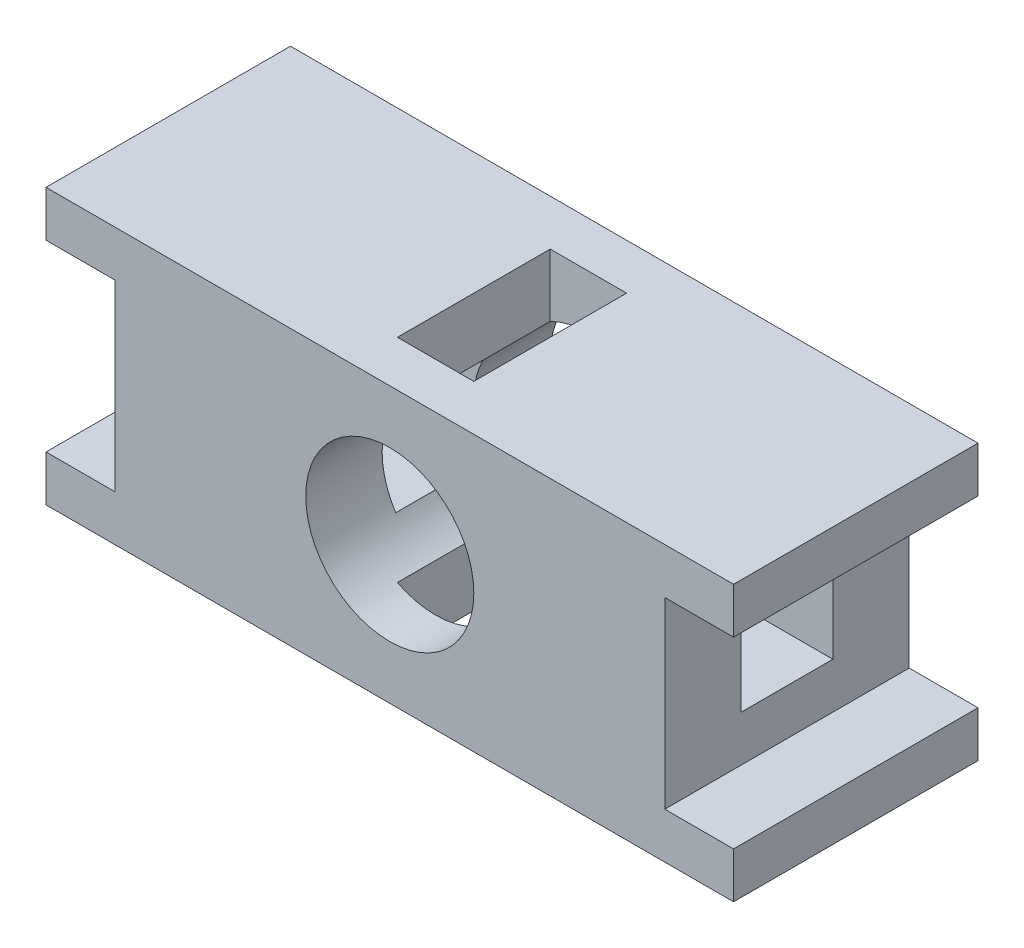
SolidWorks part; units mm, degrees
ref_plane "Спереди" through (0, 0, 0) normal (0, 0, 1) x (1, 0, 0)
ref_plane "Сверху" through (0, 0, 0) normal (0, 1, 0) x (1, 0, 0)
ref_plane "Справа" through (0, 0, 0) normal (1, 0, 0) x (0, 0, -1)
sketch "Эскиз2" plane through (0, 0, 0) normal (0, 0, 1) x (1, 0, 0)
  line L1 (-45, -18) -> (45, -18)
  line L2 (-45, -18) -> (-45, 18)
  line L3 (-45, 18) -> (45, 18)
  line L4 (45, -18) -> (45, 18)
  line L5 (-45, -18) -> (45, 18) construction
  line L6 (-45, 18) -> (45, -18) construction
  point P0 (0, 0)
  dimension "D1" = 90
  dimension "D2" = 36
extrude "Бобышка-Вытянуть1" add sketch "Эскиз2" along normal blind 32
sketch "Эскиз3" plane through (0, 0, 32) normal (0, 0, 1) x (1, 0, 0)
  line L0 (-45, 12) -> (-36, 12)
  line L1 (-45, 18) -> (-45, -18) construction
  line L2 (45, 18) -> (-45, 18) construction
  line L3 (-36, 12) -> (-36, -12)
  line L4 (-36, -12) -> (-45, -12)
  line L5 (-45, -18) -> (45, -18) construction
  line L6 (-45, 12) -> (-45, -12)
  dimension "D1" = 9
  dimension "D2" = 6
  dimension "D3" = 24
  dimension "D4" = 9
  dimension "D5" = 6
extrude "Вырез-Вытянуть1" cut sketch "Эскиз3" against normal through all
sketch "Эскиз4" plane through (0, 0, 32) normal (0, 0, 1) x (1, 0, 0)
  line L0 (45, 18) -> (-45, 18) construction
  line L1 (36, 12) -> (45, 12)
  line L2 (36, 12) -> (36, -12)
  line L3 (36, -12) -> (45, -12)
  line L4 (45, 12) -> (45, -12)
  line L5 (36, 12) -> (45, -12) construction
  line L6 (36, -12) -> (45, 12) construction
  line L7 (-45, -18) -> (45, -18) construction
  line L8 (-36, -12) -> (-36, 12) construction
  line L9 (45, -18) -> (45, 18) construction
  point P0 (40.5, 0)
  dimension "D1" = 24
  dimension "D2" = 9
  dimension "D3" = 6
  dimension "D4" = 6
  dimension "D5" = 72
  dimension "D6" = 9
extrude "Вырез-Вытянуть2" cut sketch "Эскиз4" against normal through all
sketch "Эскиз6" plane through (0, 0, 32) normal (0, 0, 1) x (1, 0, 0)
  circle A0 centre (0, 0) radius 11
  dimension "D1" = 22
extrude "Вырез-Вытянуть3" cut sketch "Эскиз6" against normal through all
sketch "Эскиз7" plane through (0, 18, 0) normal (0, 1, 0) x (1, 0, 0)
  line L0 (45, 0) -> (-45, 0) construction
  line L1 (-5, -6) -> (5, -6)
  line L2 (-5, -6) -> (-5, -26)
  line L3 (-5, -26) -> (5, -26)
  line L4 (5, -6) -> (5, -26)
  line L5 (-5, -6) -> (5, -26) construction
  line L6 (-5, -26) -> (5, -6) construction
  line L7 (45, -32) -> (-45, -32) construction
  line L8 (-45, -32) -> (-45, 0) construction
  line L9 (45, -32) -> (45, 0) construction
  point P0 (0, -16)
  dimension "D1" = 10
  dimension "D2" = 20
  dimension "D3" = 6
  dimension "D4" = 6
  dimension "D5" = 40
  dimension "D6" = 40
extrude "Вырез-Вытянуть4" cut sketch "Эскиз7" against normal through all
sketch "Эскиз9" plane through (-36, 0, 0) normal (-1, 0, 0) x (0, 0, 1)
  line L0 (0, 12) -> (32, 12) construction
  line L1 (10, 6) -> (22, 6)
  line L2 (10, 6) -> (10, -6)
  line L3 (10, -6) -> (22, -6)
  line L4 (22, 6) -> (22, -6)
  line L5 (10, 6) -> (22, -6) construction
  line L6 (10, -6) -> (22, 6) construction
  line L7 (0, -12) -> (32, -12) construction
  line L8 (0, -12) -> (0, 12) construction
  line L9 (32, -12) -> (32, 12) construction
  point P0 (16, 0)
  dimension "D1" = 12
  dimension "D2" = 12
  dimension "D3" = 6
  dimension "D4" = 6
  dimension "D5" = 10
  dimension "D6" = 10
extrude "Вырез-Вытянуть5" cut sketch "Эскиз9" against normal through all
